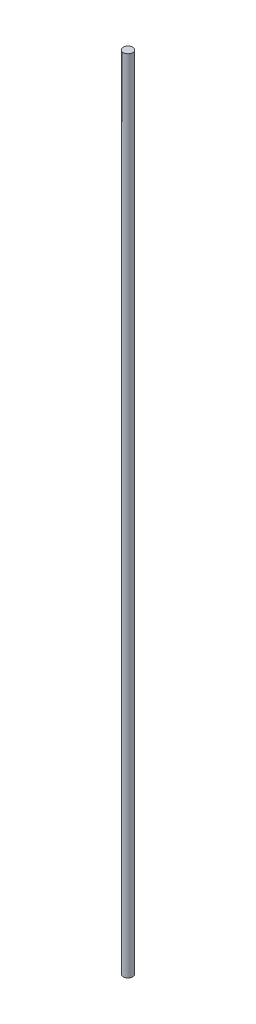
SolidWorks part; units mm, degrees
ref_plane "前视基准面" through (0, 0, 0) normal (0, 0, 1) x (1, 0, 0)
ref_plane "上视基准面" through (0, 0, 0) normal (0, 1, 0) x (1, 0, 0)
ref_plane "右视基准面" through (0, 0, 0) normal (1, 0, 0) x (0, 0, -1)
other "Configuration Table"
sketch "草图1" plane through (0, 0, 0) normal (0, 1, 0) x (1, 0, 0)
  circle A0 centre (0, 0) radius 0.5
extrude "凸台-拉伸1" add sketch "草图1" along normal blind 84
